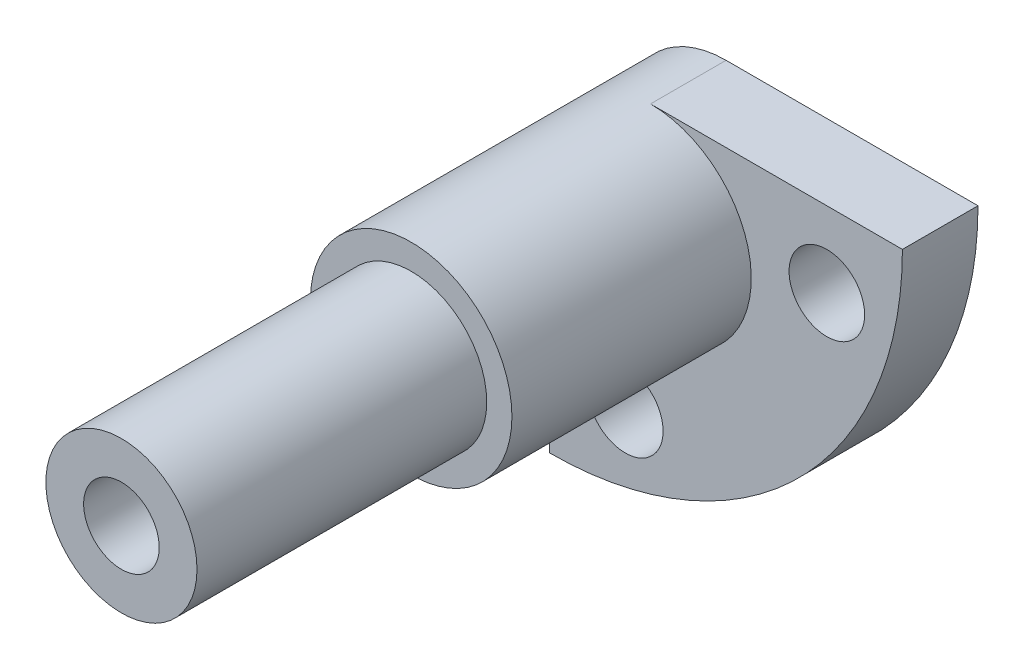
SolidWorks part; units mm, degrees
material "AISI 1020"
ref_plane "Front" through (0, 0, 0) normal (0, 0, 1) x (1, 0, 0)
ref_plane "Top" through (0, 0, 0) normal (0, 1, 0) x (1, 0, 0)
ref_plane "Right" through (0, 0, 0) normal (1, 0, 0) x (0, 0, -1)
sketch "Sketch1" plane through (0, 0, 0) normal (0, 0, 1) x (1, 0, 0)
  line L1 (10, 4) -> (0, 4)
  line L2 (-4, 0) -> (-4, -10)
  arc A0 (0, 4) -> (-4, 0) centre (0, 0) ccw
  arc A1 (10, 4) -> (-4, -10) centre (-4, 4) cw
  dimension "D1" = 4
  dimension "D2" = 14
  dimension "D3" = 10
  dimension "D4" = 10
extrude "Extrude1" add sketch "Sketch1" along normal blind 3
sketch "Sketch2" plane through (0, 0, 3) normal (0, 0, 1) x (1, 0, 0)
  circle A0 centre (0, 0) radius 4
extrude "Extrude2" add sketch "Sketch2" along normal blind 9.5
sketch "Sketch3" plane through (0, 0, 12.5) normal (0, 0, 1) x (1, 0, 0)
  circle A0 centre (0, 0) radius 3
  dimension "D1" = 6
extrude "Extrude3" add sketch "Sketch3" along normal blind 11.5
sketch "Sketch4" plane through (0, 0, 24) normal (0, 0, 1) x (1, 0, 0)
  circle A0 centre (0, 0) radius 1.5
  dimension "D1" = 3
extrude "Extrude4" cut sketch "Sketch4" against normal up to surface (24 mm away) up to face at (1.0178, -1.0178, 0)
sketch "Sketch5" plane through (0, 0, 3) normal (0, 0, 1) x (1, 0, 0)
  line L0 (10, 4) -> (0, 4) construction
  line L2 (-4, 0) -> (-4, -10) construction
  circle A0 centre (7, 1) radius 1.5
  circle A1 centre (-1, -7) radius 1.5
  dimension "D1" = 3
  dimension "D3" = 3
  dimension "D2" = 3
  dimension "D4" = 3
  dimension "D5" = 3
  dimension "D6" = 3
extrude "Extrude5" cut sketch "Sketch5" against normal up to surface (3 mm away) up to face at (1.5, 0, 0)
